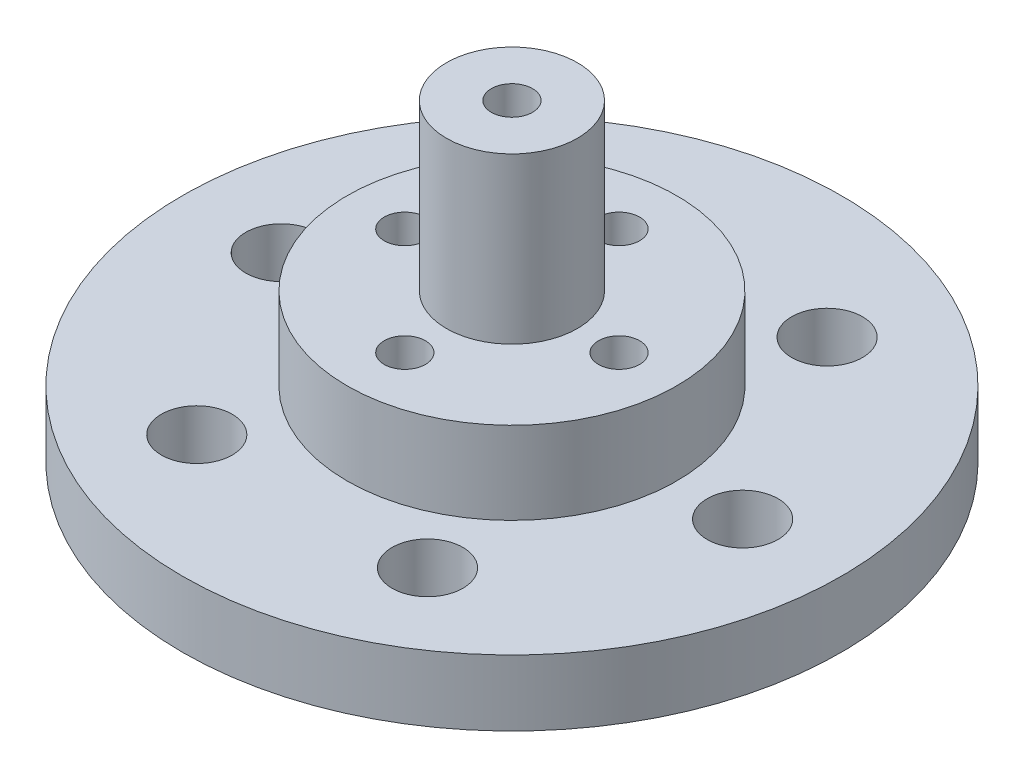
SolidWorks part; units mm, degrees
ref_plane "Front Plane" through (0, 0, 0) normal (0, 0, 1) x (1, 0, 0)
ref_plane "Top Plane" through (0, 0, 0) normal (0, 1, 0) x (1, 0, 0)
ref_plane "Right Plane" through (0, 0, 0) normal (1, 0, 0) x (0, 0, -1)
sketch "Sketch1" plane through (0, 0, 0) normal (0, 1, 0) x (1, 0, 0)
  circle A0 centre (0, 0) radius 20
  dimension "D1" = 40
extrude "Boss-Extrude1" add sketch "Sketch1" along normal blind 4
sketch "Sketch2" plane through (0, 4, 0) normal (0, 1, 0) x (1, 0, 0)
  circle A0 centre (0, 0) radius 10
  dimension "D1" = 20
extrude "Boss-Extrude2" add sketch "Sketch2" along normal blind 5
sketch "Sketch3" plane through (0, 4, 0) normal (0, 1, 0) x (1, 0, 0)
  circle A0 centre (0, 0) radius 14 construction
  dimension "D1" = 28
sketch "Sketch4" plane through (0, 9, 0) normal (0, 1, 0) x (1, 0, 0)
  circle A0 centre (0, 0) radius 3.975
  dimension "D1" = 7.95
extrude "Boss-Extrude3" add sketch "Sketch4" along normal blind 10
hole_wizard "M4 Clearance Hole2" positions "Sketch5" profile "Sketch6" hole size "M4" standard "ISO" end condition through all
sketch "Sketch5" plane through (0, 4, 0) normal (0, 1, 0) x (1, 0, 0)
  circle A0 centre (0, 0) radius 14 construction
  point P0 (-14, 0)
  point P13 (-7, 12.1244)
  point P14 (7, 12.1244)
  point P15 (14, 0)
  point P16 (7, -12.1244)
  point P17 (-7, -12.1244)
  dimension "D2" = 60
  dimension "D1" = 6
sketch "Sketch6" plane through (-14, 4, 0) normal (1, 0, 0) x (0, 0, 1)
  line L0 (0, 0) -> (0, 4)
  line L1 (0, 4) -> (2.15, 4)
  line L2 (2.15, 4) -> (2.15, 0)
  line L5 (2.15, 0) -> (0, 0)
  line L11 (0, -6.35) -> (0, 107.95) construction
  dimension "Thru Hole Dia." = 4.3
  dimension "Thru Hole Depth" = 4
sketch "Sketch7" plane through (0, 9, 0) normal (0, 1, 0) x (1, 0, 0)
  circle A0 centre (0, 0) radius 6.5 construction
  dimension "D1" = 13
hole_wizard "M3 Tapped Hole1" positions "Sketch8" profile "Sketch9" tap size "M3" standard "ISO"
sketch "Sketch8" plane through (0, 9, 0) normal (0, 1, 0) x (1, 0, 0)
  circle A0 centre (0, 0) radius 6.5 construction
  point P0 (-6.5, 0)
  point P19 (0, 6.5)
  point P20 (6.5, 0)
  point P21 (0, -6.5)
  point P23 (0, 0)
  dimension "D2" = 90
  dimension "D1" = 4
sketch "Sketch9" plane through (-6.5, 9, 0) normal (1, 0, 0) x (0, 0, 1)
  line L0 (0, 0) -> (0, 5.7511)
  line L1 (0, 5.7511) -> (1.25, 5)
  line L2 (1.25, 5) -> (1.25, 0)
  line L5 (1.25, 0) -> (0, 0)
  line L10 (0, 5.7511) -> (-1.25, 5) construction
  line L11 (0, -6.35) -> (0, 107.95) construction
  dimension "Tap Drill Dia." = 2.5
  dimension "Tap Drill Depth" = 5
  dimension "Drill Angle" = 118
cosmetic thread "Hole Thread1" parameters "D1"=6, "D2"=3
cosmetic thread "Hole Thread2" parameters "D1"=6, "D2"=3
cosmetic thread "Hole Thread3" parameters "D1"=6, "D2"=3
cosmetic thread "Hole Thread4" parameters "D1"=6, "D2"=3
hole_wizard "M3 Tapped Hole2" positions "Sketch10" profile "Sketch11" tap size "M3" standard "ISO"
sketch "Sketch10" plane through (0, 19, 0) normal (0, 1, 0) x (1, 0, 0)
  point P0 (0, 0)
cosmetic thread "Hole Thread5" parameters "D1"=19, "D2"=3
sketch "Sketch11" plane through (0, 19, 0) normal (1, 0, 0) x (0, 0, 1)
  line L0 (0, 0) -> (0, 5.7511)
  line L1 (0, 5.7511) -> (1.25, 5)
  line L2 (1.25, 5) -> (1.25, 0)
  line L5 (1.25, 0) -> (0, 0)
  line L10 (0, 5.7511) -> (-1.25, 5) construction
  line L11 (0, -6.35) -> (0, 107.95) construction
  dimension "Tap Drill Dia." = 2.5
  dimension "Tap Drill Depth" = 5
  dimension "Drill Angle" = 118
